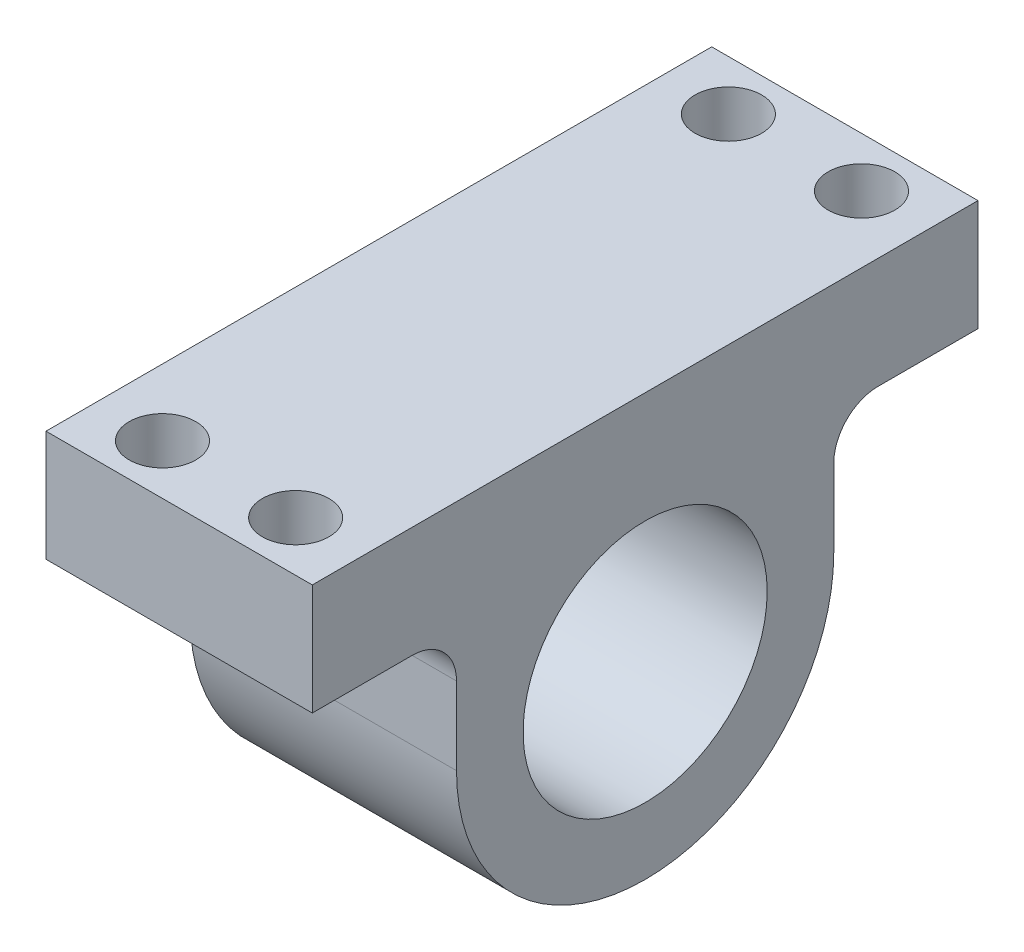
SolidWorks part; units mm, degrees
ref_plane "前视基准面" through (0, 0, 0) normal (0, 0, 1) x (1, 0, 0)
ref_plane "上视基准面" through (0, 0, 0) normal (0, 1, 0) x (1, 0, 0)
ref_plane "右视基准面" through (0, 0, 0) normal (1, 0, 0) x (0, 0, -1)
sketch "草图2" plane through (0, 0, 0) normal (1, 0, 0) x (0, 0, -1)
  line L1 (-15, 5.5) -> (-15, 10.5)
  line L2 (-15, 10.5) -> (15, 10.5)
  line L3 (15, 10.5) -> (15, 5.5)
  line L4 (-15, 5.5) -> (-10.5, 5.5)
  line L5 (10.5, 5.5) -> (15, 5.5)
  line L6 (-8.5, 0) -> (-8.5, 3.5)
  line L7 (8.5, 0) -> (8.5, 3.5)
  circle A0 centre (0, 0) radius 5.5
  arc A1 (-8.5, 0) -> (8.5, 0) centre (0, 0) ccw
  arc A2 (8.5, 3.5) -> (10.5, 5.5) centre (10.5, 3.5) cw
  arc A3 (-10.5, 5.5) -> (-8.5, 3.5) centre (-10.5, 3.5) cw
  point P6 (0, 5.5)
  dimension "D1" = 30
  dimension "D2" = 2
  dimension "D3" = 2
  dimension "D4" = 5
extrude "凸台-拉伸1" add sketch "草图2" along normal blind 12
sketch "草图5" plane through (0, 5.5, 0) normal (0, -1, 0) x (1, 0, 0)
  line L0 (0, 15) -> (2.5, 15)
  line L1 (12, 15) -> (0, 15) construction
  line L2 (0, 12.75) -> (3, 12.75)
  line L3 (0, 15) -> (0, 10.5) construction
  line L4 (12, 12.75) -> (9, 12.75)
  line L5 (12, 15) -> (12, 10.5) construction
  line L6 (0, 0) -> (12, 0) construction
  line L7 (12, -8.5) -> (12, 8.5) construction
  circle A0 centre (3, 12.75) radius 1.5
  circle A1 centre (9, 12.75) radius 1.5
  circle A2 centre (9, -12.75) radius 1.5
  circle A3 centre (3, -12.75) radius 1.5
extrude "切除-拉伸1" cut sketch "草图5" against normal blind 5
